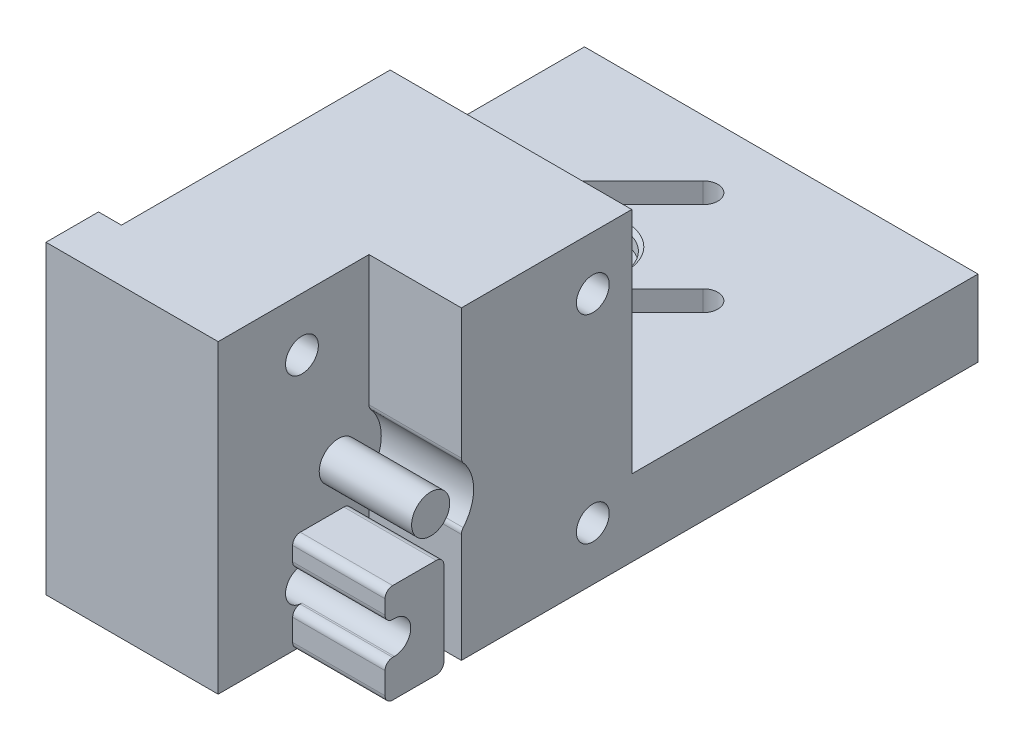
SolidWorks part; units mm, degrees
material "AISI 1045 Steel, cold drawn"
ref_plane "Front Plane" through (0, 0, 0) normal (0, 0, 1) x (1, 0, 0)
ref_plane "Top Plane" through (0, 0, 0) normal (0, 1, 0) x (1, 0, 0)
ref_plane "Right Plane" through (0, 0, 0) normal (1, 0, 0) x (0, 0, -1)
sketch "Sketch1" plane through (0, 0, 0) normal (0, 1, 0) x (1, 0, 0)
  line L0 (-211.9, -221.9) -> (-183.9, -221.9) construction
  line L1 (250, -250) -> (-250, -250)
  line L2 (250, -250) -> (250, 250)
  line L3 (250, 250) -> (-250, 250)
  line L4 (-250, -250) -> (-250, 250)
  line L5 (250, -250) -> (-250, 250) construction
  line L6 (250, 250) -> (-250, -250) construction
  line L7 (-250, -250) -> (-211.9, -250)
  line L8 (-250, -250) -> (-250, -211.9)
  line L9 (-250, -211.9) -> (-211.9, -211.9)
  line L10 (-211.9, -250) -> (-211.9, -211.9)
  line L11 (-211.9, -239) -> (-183.9, -239)
  line L12 (-211.9, -239) -> (-211.9, -204.8)
  line L13 (-211.9, -204.8) -> (-183.9, -204.8)
  line L14 (-183.9, -239) -> (-183.9, -204.8)
  line L16 (152.5, 152.5) -> (-152.5, 152.5)
  line L17 (152.5, 152.5) -> (152.5, -152.5)
  line L18 (152.5, -152.5) -> (-152.5, -152.5)
  line L19 (-152.5, 152.5) -> (-152.5, -152.5)
  line L20 (152.5, 152.5) -> (-152.5, -152.5) construction
  line L21 (152.5, -152.5) -> (-152.5, 152.5) construction
  point P0 (0, 0)
  point P15 (-158.3, -233)
  point P16 (-188.9, -188.9)
  point P17 (0, 0)
  point P22 (-181.1218, -181.1218)
  dimension "D1" = 500
  dimension "D2" = 38.1
  dimension "D3" = 28
  dimension "D4" = 34.2
  dimension "D5" = 20
  dimension "D6" = 91.7
  dimension "D7" = 17
  dimension "D8" = 305
  dimension "D9" = 5
  dimension "D10" = 11
ref_plane "Plane1" through (-188.9, 0, 188.9) normal (-0.7071, 0, 0.7071) x (0.7071, 0, 0.7071)
sketch "Sketch3" plane through (-188.9, 0, 188.9) normal (-0.7071, 0, 0.7071) x (0.7071, 0, 0.7071)
  line L0 (-8.6603, -5) -> (8.6603, -5) construction
  line L1 (0, 0) -> (0, -5) construction
  line L2 (-8.6603, -5) -> (0, 0) construction
  line L3 (-6.7451, -6.607) -> (-8.6603, -5) construction
  line L4 (-6.7451, -6.607) -> (6.7451, -6.607)
  line L5 (-6.7451, -6.607) -> (-6.7451, -16.607)
  line L6 (-6.7451, -16.607) -> (6.7451, -16.607)
  line L7 (6.7451, -6.607) -> (6.7451, -16.607)
  line L8 (10.5754, -16.607) -> (13.5754, -16.607)
  line L9 (-10.5754, -6.607) -> (-13.5754, -6.607)
  line L10 (-10.5754, -6.607) -> (-10.5754, -16.607)
  line L11 (-10.5754, -16.607) -> (-13.5754, -16.607)
  line L12 (-13.5754, -6.607) -> (-13.5754, -16.607)
  line L13 (13.5754, -6.607) -> (13.5754, -16.607)
  line L14 (10.5754, -6.607) -> (13.5754, -6.607)
  line L15 (10.5754, -6.607) -> (10.5754, -16.607)
  circle A0 centre (0, 0) radius 7.5
  circle A1 centre (-8.6603, -5) radius 2.5
  circle A2 centre (8.6603, -5) radius 2.5
  point P20 (-10.5754, -3.393)
  dimension "D1" = 15
  dimension "D2" = 5
  dimension "D3" = 30
  dimension "D4" = 10
  dimension "D5" = 40
  dimension "D6" = 3
extrude "Boss-Extrude1" add sketch "Sketch3" against normal blind 22 contours L9 L12 L11 L10 | L7 L4 L5 L6 | L14 L15 L8 L13 | L4 A0
sketch "Sketch4" plane through (-188.9, 0, 188.9) normal (-0.7071, 0, 0.7071) x (0.7071, 0, 0.7071)
  line L1 (-13.5754, -16.607) -> (13.5754, -16.607)
  line L2 (-13.5754, -16.607) -> (-13.5754, -6.607)
  line L3 (-13.5754, -6.607) -> (13.5754, -6.607)
  line L4 (13.5754, -16.607) -> (13.5754, -6.607)
extrude "Boss-Extrude2" add sketch "Sketch4" along normal blind 3
sketch "Sketch5" plane through (-173.3437, 0, 173.3437) normal (0.7071, 0, -0.7071) x (-0.7071, 0, -0.7071)
  line L1 (-13.5754, -16.607) -> (13.5754, -16.607)
  line L2 (-13.5754, -16.607) -> (-13.5754, -6.607)
  line L3 (-13.5754, -6.607) -> (13.5754, -6.607)
  line L4 (13.5754, -16.607) -> (13.5754, -6.607)
extrude "Boss-Extrude3" add sketch "Sketch5" along normal blind 3
sketch "Sketch7" plane through (0, -6.607, 0) normal (0, 1, 0) x (1, 0, 0)
  line L0 (-186.9, -239) -> (-183.9, -239)
  line L1 (-211.9, -239) -> (-183.9, -239) construction
  line L2 (-183.9, -239) -> (-183.9, -203.8)
  line L4 (-186.9, -239) -> (-186.9, -245.88)
  line L5 (-186.9, -245.88) -> (-147.25, -245.88)
  line L13 (-184.6015, -203.8) -> (-161.6231, -180.8216)
  line L15 (-183.9, -203.8) -> (-200.6206, -203.8)
  line L33 (-200.6206, -203.8) -> (-200.6206, -181.4221)
  line L34 (-200.6206, -181.4221) -> (-178.2426, -203.8)
  line L35 (-211.9, -204.8) -> (-183.9, -204.8) construction
  line L37 (-152.25, -239.88) -> (-164.35, -239.88) construction
  line L38 (-152.25, -239.88) -> (-152.25, -226.12)
  line L39 (-152.25, -226.12) -> (-164.35, -226.12)
  line L40 (-164.35, -239.88) -> (-164.35, -226.12)
  line L41 (-152.25, -239.88) -> (-164.35, -226.12) construction
  line L42 (-152.25, -226.12) -> (-164.35, -239.88) construction
  line L44 (-147.25, -161.6231) -> (-147.25, -245.88)
  line L45 (-164.35, -239.88) -> (-164.35, -240.88)
  line L46 (-164.35, -240.88) -> (-152.25, -240.88)
  line L47 (-152.25, -240.88) -> (-152.25, -239.88)
  line L48 (-181.4221, -200.6206) -> (-200.6206, -181.4221) construction
  line L49 (-181.4221, -200.6206) -> (-161.6231, -180.8216) construction
  line L50 (-161.6231, -180.8216) -> (-180.8216, -161.6231)
  line L51 (-180.8216, -161.6231) -> (-147.25, -161.6231)
  point P17 (-158.3, -233)
  dimension "D3" = 1
  dimension "D4" = 13.76
  dimension "D1" = 3
  dimension "D2" = 1
  dimension "D5" = 12.1
  dimension "D7" = 5
  dimension "D8" = 5
extrude "Boss-Extrude4" add sketch "Sketch7" against normal up to surface (10 mm away) up to face at (-181.1218, -16.607, 181.1218)
sketch "Sketch13" plane through (0, -6.607, 0) normal (0, 1, 0) x (1, 0, 0)
  line L2 (-181.4221, -196.3779) -> (-181.4221, -203.8) construction
  line L3 (-200.6206, -203.8) -> (-203.8, -203.8)
  line L4 (-200.6206, -203.8) -> (-200.6206, -181.4221)
  line L5 (-180.8216, -161.6231) -> (-200.6206, -181.4221)
  line L7 (-203.8, -203.8) -> (-203.8, -158.4437)
  line L8 (-183.9, -203.8) -> (-200.6206, -203.8) construction
  line L9 (-196.3779, -181.4221) -> (-203.8, -181.4221) construction
  line L10 (-180.8216, -165.8657) -> (-180.8216, -158.4437) construction
  line L11 (-180.8216, -161.6231) -> (-147.25, -161.6231)
  line L12 (-147.25, -161.6231) -> (-147.25, -158.4437)
  line L13 (-147.25, -158.4437) -> (-203.8, -158.4437)
extrude "Boss-Extrude5" add sketch "Sketch13" against normal up to surface (10 mm away) up to face at (-179.7959, -16.607, 209.1143)
sketch "Sketch15" plane through (0, -6.607, 0) normal (0, 1, 0) x (1, 0, 0)
  line L0 (-180.8216, -165.8657) -> (-178.1132, -168.5741) construction
  line L5 (-168.5741, -178.1132) -> (-165.8657, -180.8216) construction
  line L10 (-193.6695, -184.1305) -> (-196.3779, -181.4221) construction
  line L11 (-181.4221, -196.3779) -> (-184.1305, -193.6695) construction
  circle A8 centre (-179.4674, -167.2199) radius 1.9151
  circle A9 centre (-167.2199, -179.4674) radius 1.9151
  circle A10 centre (-195.0237, -182.7763) radius 1.9151
  circle A11 centre (-182.7763, -195.0237) radius 1.9151
extrude "Cut-Extrude4" cut sketch "Sketch15" against normal through all
sketch "Sketch18" plane through (0, -6.607, 0) normal (0, 1, 0) x (1, 0, 0)
  line L0 (-183.9, -203.8) -> (-147.25, -203.8)
  line L1 (-152.25, -226.12) -> (-164.35, -226.12) construction
  line L2 (-164.35, -226.12) -> (-164.35, -240.88) construction
  line L3 (-164.35, -240.88) -> (-152.25, -240.88) construction
  line L4 (-152.25, -240.88) -> (-152.25, -226.12) construction
  line L5 (-152.25, -226.12) -> (-164.35, -226.12)
  line L6 (-164.35, -226.12) -> (-164.35, -240.88)
  line L7 (-164.35, -240.88) -> (-152.25, -240.88)
  line L8 (-147.25, -245.88) -> (-147.25, -158.4437)
  line L9 (-147.25, -158.4437) -> (-203.8, -158.4437)
  line L10 (-203.8, -158.4437) -> (-203.8, -203.8)
  line L11 (-203.8, -203.8) -> (-183.9, -203.8)
  line L12 (-183.9, -203.8) -> (-183.9, -239)
  line L13 (-183.9, -239) -> (-186.9, -239)
  line L14 (-186.9, -239) -> (-186.9, -245.88)
  line L15 (-186.9, -245.88) -> (-147.25, -245.88)
  line L16 (-147.25, -245.88) -> (-147.25, -203.8)
  line L20 (-183.9, -203.8) -> (-183.9, -239)
  line L21 (-183.9, -239) -> (-186.9, -239)
  line L22 (-186.9, -239) -> (-186.9, -245.88)
  line L23 (-186.9, -245.88) -> (-147.25, -245.88)
  line L24 (-152.25, -240.88) -> (-152.25, -226.12)
  dimension "D1" = 0
extrude "Boss-Extrude6" add sketch "Sketch18" along normal blind 30
hole_wizard "M4 Clearance Hole1" positions "Sketch19" profile "Sketch21" hole size "M4" standard "ANSI Metric" end condition through all
sketch "Sketch19" plane through (-147.25, 0, 0) normal (1, 0, 0) x (0, 0, -1)
  line L1 (-234.9, 16.393) -> (-208.9, 16.393)
  line L2 (-234.9, 16.393) -> (-234.9, -9.607)
  line L3 (-234.9, -9.607) -> (-208.9, -9.607)
  line L4 (-208.9, 16.393) -> (-208.9, -9.607)
  line L5 (-239, -16.607) -> (-239, 23.393) construction
  line L6 (-245.88, 23.393) -> (-245.88, -16.607) construction
  point P1 (-234.9, 16.393)
  point P2 (-208.9, -9.607)
  point P123 (-234.9, -9.607)
  point P124 (-208.9, 16.393)
  point P146 (-245.88, 3.393)
  point P147 (-234.9, 3.393)
  dimension "D1" = 26
  dimension "D2" = 26
  dimension "D3" = 4.1
sketch "Sketch21" plane through (-147.25, 16.393, 234.9) normal (0, 1, 0) x (0, 0, -1)
  line L0 (0, 0) -> (0, 56.55)
  line L1 (0, 56.55) -> (2.15, 56.55)
  line L2 (2.15, 56.55) -> (2.15, 0)
  line L5 (2.15, 0) -> (0, 0)
  line L11 (0, -6.35) -> (0, 107.95) construction
  dimension "Thru Hole Dia." = 4.3
  dimension "Thru Hole Depth" = 56.55
sketch "Sketch22" plane through (-147.25, 0, 0) normal (1, 0, 0) x (0, 0, -1)
  line L6 (-245.88, 23.393) -> (-245.88, -16.607)
  line L7 (-245.88, -16.607) -> (-158.4437, -16.607)
  line L8 (-158.4437, -16.607) -> (-158.4437, -6.607)
  line L9 (-158.4437, -6.607) -> (-203.8, -6.607)
  line L10 (-203.8, -6.607) -> (-203.8, 23.393)
  line L11 (-203.8, 23.393) -> (-245.88, 23.393)
  line L12 (-245.88, 23.393) -> (-245.88, -16.607)
  line L13 (-245.88, -16.607) -> (-158.4437, -16.607)
  line L14 (-158.4437, -16.607) -> (-158.4437, -6.607)
  line L15 (-158.4437, -6.607) -> (-203.8, -6.607)
  line L16 (-203.8, -6.607) -> (-203.8, 23.393)
  line L17 (-203.8, 23.393) -> (-245.88, 23.393)
  dimension "D1" = 0
extrude "Cut-Extrude7" cut sketch "Sketch22" against normal blind 5
sketch "Sketch17" plane through (0, -6.607, 0) normal (0, 1, 0) x (1, 0, 0)
  line L0 (-185.8914, -176.3523) -> (-176.3523, -185.8914) construction
  line L1 (-178.1132, -168.5741) -> (-193.6695, -184.1305) construction
  line L2 (-168.5741, -178.1132) -> (-184.1305, -193.6695) construction
  circle A0 centre (-181.1218, -181.1218) radius 5
  dimension "D1" = 10
extrude "Cut-Extrude6" cut sketch "Sketch17" against normal blind 2
chamfer "Chamfer1" distance 0.5 angle 45 1 edges at (-181.1218, -6.607, 186.1218)
sketch "Sketch24" plane through (-152.25, 0, 0) normal (1, 0, 0) x (0, 0, -1)
  line L4 (-240.88, -16.607) -> (-240.88, 23.393)
  line L5 (-240.88, 23.393) -> (-245.88, 23.393)
  line L6 (-245.88, 23.393) -> (-245.88, -16.607)
  line L7 (-245.88, -16.607) -> (-240.88, -16.607)
  line L8 (-240.88, -16.607) -> (-240.88, 23.393)
  line L9 (-240.88, 23.393) -> (-245.88, 23.393)
  line L10 (-245.88, 23.393) -> (-245.88, -16.607)
  line L11 (-245.88, -16.607) -> (-240.88, -16.607)
  dimension "D1" = 0
extrude "Cut-Extrude8" cut sketch "Sketch24" against normal up to surface (12.1 mm away) up to face at (-164.35, 14.243, 234.9)
sketch "Sketch25" plane through (-164.35, 0, 0) normal (1, 0, 0) x (0, 0, -1)
  line L0 (-228.41, -16.607) -> (-228.41, -1.607) construction
  line L1 (-245.88, -16.607) -> (-226.12, -16.607) construction
  line L2 (-226.12, -16.607) -> (-226.12, 23.393) construction
  line L3 (-226.12, -16.607) -> (-226.12, 23.393) construction
  line L4 (-228.41, -3.607) -> (-236.12, -3.607)
  line L5 (-236.12, -3.607) -> (-236.12, -7.457)
  line L6 (-236.12, -16.607) -> (-228.41, -16.607)
  line L7 (-228.41, -16.607) -> (-228.41, -3.607)
  line L8 (-236.12, -11.757) -> (-236.12, -16.607)
  line L9 (-234.9, -7.457) -> (-236.12, -7.457)
  line L10 (-234.9, -11.757) -> (-236.12, -11.757)
  circle A0 centre (-230.14, 2.0217) radius 2.5
  circle A1 centre (-230.14, 2.0217) radius 4.02 construction
  circle A2 centre (-234.9, -9.607) radius 2.15 construction
  arc A3 (-234.9, -11.757) -> (-234.9, -7.457) centre (-234.9, -9.607) ccw
  dimension "D1" = 5
  dimension "D3" = 1.52
  dimension "D2" = 2.29
  dimension "D4" = 15
  dimension "D5" = 13
  dimension "D6" = 10
extrude "Boss-Extrude10" add sketch "Sketch25" along normal up to surface (12.1 mm away) up to face at (-152.25, 16.393, 206.75)
sketch "Sketch31" plane through (-152.25, 0, 0) normal (1, 0, 0) x (0, 0, -1)
  line L0 (-228.41, -3.607) -> (-236.12, -3.607) construction
  circle A0 centre (-230.14, 2.0217) radius 5.6287
  circle A1 centre (-230.14, 2.0217) radius 2.5 construction
  circle A2 centre (-230.14, 2.0217) radius 2.5
extrude "Cut-Extrude10" cut sketch "Sketch31" against normal up to surface (12.1 mm away) up to face at (-164.35, 14.243, 234.9)
fillet "Fillet1" radius 1 7 edges at (-158.3, -3.607, 228.41) (-158.3, -16.607, 236.12) (-158.3, -16.607, 228.41) (-158.3, -11.757, 236.12) (-158.3, -7.457, 236.12) (-158.3, -3.607, 236.12) (-158.3, -1.9181, 226.12)
sketch "Sketch23" plane through (-164.35, 0, 0) normal (1, 0, 0) x (0, 0, -1)
  line L0 (-230.3615, -8.0781) -> (-230.3615, -8.3379)
  line L1 (-231.1115, -7.3379) -> (-230.3615, -7.3379) construction
  line L2 (-230.3615, -8.3379) -> (-231.1115, -8.3379)
  line L3 (-231.1115, -8.3379) -> (-231.1115, -6.3379)
  line L4 (-230.3615, -6.3379) -> (-231.1115, -6.3379)
  line L5 (-230.3615, -6.5977) -> (-230.3615, -6.3379)
  arc A0 (-230.7997, -6.839) -> (-230.7997, -7.8368) centre (-230.5565, -7.3379) ccw
  arc A1 (-230.7997, -7.8368) -> (-230.4919, -7.9293) centre (-230.3615, -6.9379) ccw
  arc A2 (-230.3615, -8.0781) -> (-230.4919, -7.9293) centre (-230.5115, -8.0781) ccw
  arc A3 (-230.3615, -6.5977) -> (-230.4919, -6.7464) centre (-230.5115, -6.5977) cw
  arc A4 (-230.7997, -6.839) -> (-230.4919, -6.7464) centre (-230.3615, -7.7379) cw
  point P6 (-231.1115, -7.3379)
  point P18 (0, 0)
  point P19 (0, 0)
  point P20 (-231.1115, -6.3379)
  point P22 (-226.89, -7.6523)
  point P23 (-227.64, -9.0153)
  dimension "D1" = 0.555
  dimension "D2" = 0.15
  dimension "D4" = 1
  dimension "D3" = 1
  dimension "D5" = 0.75
  dimension "D6" = 0.4
